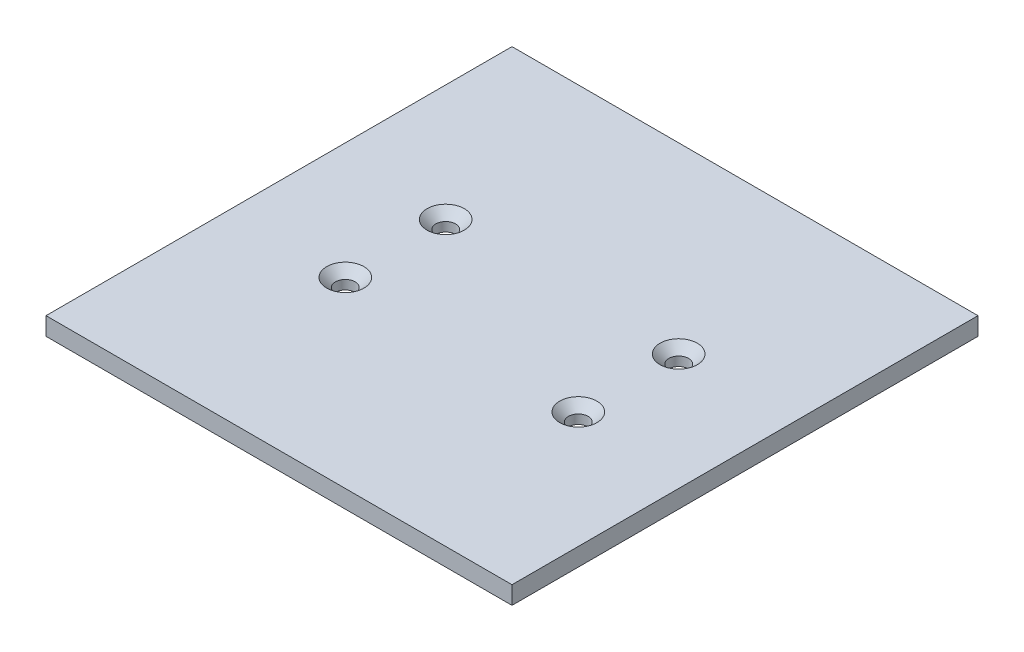
SolidWorks part; units mm, degrees
material "PTFE generico"
ref_plane "Piano frontale" through (0, 0, 0) normal (0, 0, 1) x (1, 0, 0)
ref_plane "Piano superiore" through (0, 0, 0) normal (0, 1, 0) x (1, 0, 0)
ref_plane "Piano destro" through (0, 0, 0) normal (1, 0, 0) x (0, 0, -1)
sketch "Schizzo1" plane through (0, 0, 0) normal (0, 1, 0) x (1, 0, 0)
  line L0 (-83.9788, 0) -> (95.4197, 0) construction
  line L1 (-65, 65) -> (65, 65)
  line L2 (-65, 65) -> (-65, -65)
  line L3 (-65, -65) -> (65, -65)
  line L4 (65, 65) -> (65, -65)
  line L5 (0, -70.8918) -> (0, 73.0155) construction
  point P10 (0, 65)
  point P11 (-65, 0)
  dimension "D1" = 130
  dimension "D2" = 130
extrude "Estrusione-Estrusione1" add sketch "Schizzo1" along normal blind 5
sketch "Schizzo3" plane through (0, 5, 0) normal (0, 1, 0) x (1, 0, 0)
  line L0 (0, 65) -> (0, -65) construction
  line L1 (65, 65) -> (-65, 65) construction
  line L2 (-65, -65) -> (65, -65) construction
  line L3 (-65, 0) -> (65, 0) construction
  line L4 (-65, 65) -> (-65, -65) construction
  line L5 (65, -65) -> (65, 65) construction
  line L6 (-65, -14) -> (65, -14) construction
  line L7 (-65, 14) -> (65, 14) construction
  line L8 (-32.5, 65) -> (-32.5, -65) construction
  line L9 (32.5, 65) -> (32.5, -65) construction
  dimension "D1" = 14
  dimension "D2" = 32.5
hole_wizard "Foro svasato per Vite M5-1" positions "Schizzo3D1" profile "Schizzo4" countersink size "M5" standard "ISO" end condition through all
sketch3d "Schizzo3D1"
  line L0 (-65, 5, -14) -> (65, 5, -14) construction
  line L1 (-32.5, 5, -65) -> (-32.5, 5, 65) construction
  line L2 (32.5, 5, -65) -> (32.5, 5, 65) construction
  line L3 (-65, 5, 14) -> (65, 5, 14) construction
  point P0 (-32.5, 5, -14)
  point P6 (32.5, 5, -14)
  point P10 (32.5, 5, 14)
  point P14 (-32.5, 5, 14)
sketch "Schizzo4" plane through (-32.5, 5, -14) normal (1, 0, 0) x (0, 0, 1)
  line L0 (0, 0) -> (0, 5)
  line L1 (0, 5) -> (2.75, 5)
  line L2 (2.75, 5) -> (2.75, 2.45)
  line L3 (2.75, 2.45) -> (5.2, 0)
  line L5 (5.2, 0) -> (0, 0)
  line L6 (-2.75, 2.45) -> (-5.2, 0) construction
  line L11 (0, -6.35) -> (0, 107.95) construction
  dimension "Thru Hole Dia." = 5.5
  dimension "Thru Hole Depth" = 5
  dimension "Near C'Sink Dia." = 10.4
  dimension "Near C'Sink Angle" = 90
